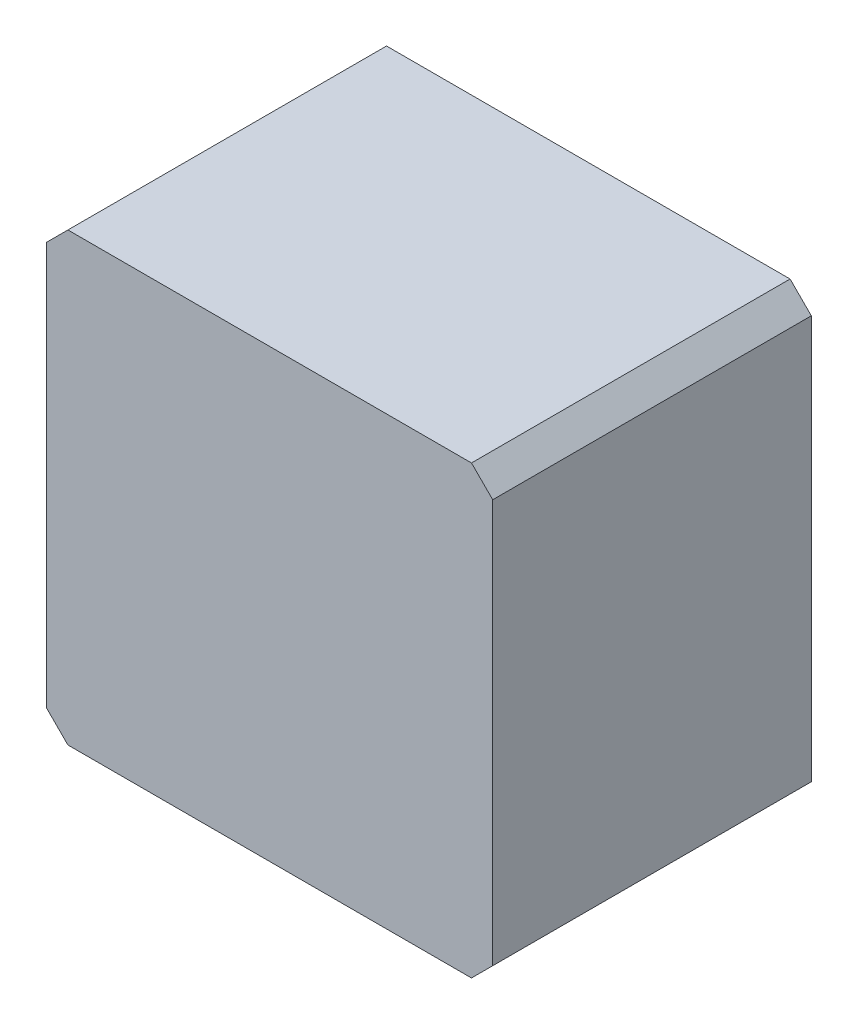
SolidWorks part; units mm, degrees
material "BUTYL"
ref_plane "Front Plane" through (0, 0, 0) normal (0, 0, 1) x (1, 0, 0)
ref_plane "Top Plane" through (0, 0, 0) normal (0, 1, 0) x (1, 0, 0)
ref_plane "Right Plane" through (0, 0, 0) normal (1, 0, 0) x (0, 0, -1)
sketch "Sketch1" plane through (0, 0, 0) normal (0, 0, 1) x (1, 0, 0)
  line L0 (-21, 19) -> (-19, 21)
  line L1 (-19, 21) -> (19, 21)
  line L2 (-21, 19) -> (-21, -19)
  line L3 (-19, -21) -> (19, -21)
  line L4 (21, 19) -> (21, -19)
  line L5 (-21, 21) -> (21, -21) construction
  line L6 (-21, -21) -> (21, 21) construction
  line L7 (-21, -19) -> (-19, -21)
  line L8 (21, -19) -> (19, -21)
  line L9 (19, 21) -> (21, 19)
  point P0 (0, 0)
  dimension "D1" = 42
  dimension "D2" = 42
extrude "Boss-Extrude1" add sketch "Sketch1" along normal blind 30
